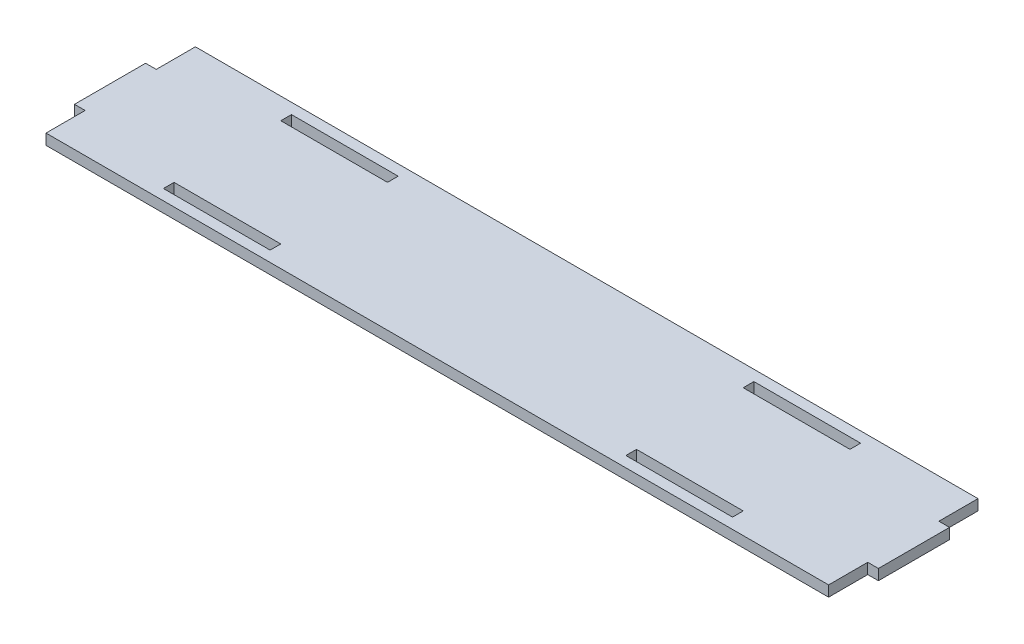
SolidWorks part; units mm, degrees
material "ABS"
ref_plane "Front Plane" through (0, 0, 0) normal (0, 0, 1) x (1, 0, 0)
ref_plane "Top Plane" through (0, 0, 0) normal (0, 1, 0) x (1, 0, 0)
ref_plane "Right Plane" through (0, 0, 0) normal (1, 0, 0) x (0, 0, -1)
sketch "Sketch1" plane through (0, 0, 0) normal (0, 1, 0) x (1, 0, 0)
  line L0 (0, 21) -> (220, 21) construction
  line L1 (0, 0) -> (220, 0)
  line L2 (0, 0) -> (0, 11)
  line L3 (0, 42) -> (220, 42)
  line L4 (220, 0) -> (220, 11)
  line L5 (30, 39) -> (60, 39)
  line L6 (30, 39) -> (30, 36)
  line L7 (30, 36) -> (60, 36)
  line L8 (60, 39) -> (60, 36)
  line L9 (160, 39) -> (190, 39)
  line L10 (160, 39) -> (160, 36)
  line L11 (160, 36) -> (190, 36)
  line L12 (190, 39) -> (190, 36)
  line L13 (190, 3) -> (190, 6)
  line L14 (160, 6) -> (190, 6)
  line L15 (160, 3) -> (160, 6)
  line L16 (160, 3) -> (190, 3)
  line L17 (60, 3) -> (60, 6)
  line L18 (30, 3) -> (30, 6)
  line L19 (30, 6) -> (60, 6)
  line L20 (30, 3) -> (60, 3)
  line L21 (0, 31) -> (0, 42)
  line L22 (220, 31) -> (223, 31)
  line L24 (220, 11) -> (223, 11)
  line L25 (223, 31) -> (223, 11)
  line L26 (0, 31) -> (-3, 31)
  line L28 (0, 11) -> (-3, 11)
  line L29 (-3, 31) -> (-3, 11)
  line L30 (220, 31) -> (220, 42)
  dimension "D1" = 42
  dimension "D2" = 220
  dimension "D3" = 30
  dimension "D4" = 30
  dimension "D5" = 3
  dimension "D6" = 3
  dimension "D7" = 3
  dimension "D8" = 30
  dimension "D9" = 3
  dimension "D10" = 30
  dimension "D11" = 20
  dimension "D12" = 3
  dimension "D13" = 11
  dimension "D14" = 20
  dimension "D15" = 3
  dimension "D16" = 11
extrude "Boss-Extrude1" add sketch "Sketch1" along normal blind 3 contours L3 L30 L22 L25 L24 L4 L1 L2 L28 L29 L26 L21 | L16 L13 L14 L15 | L9 L12 L11 L10 | L5 L8 L7 L6 | L19 L17 L20 L18
